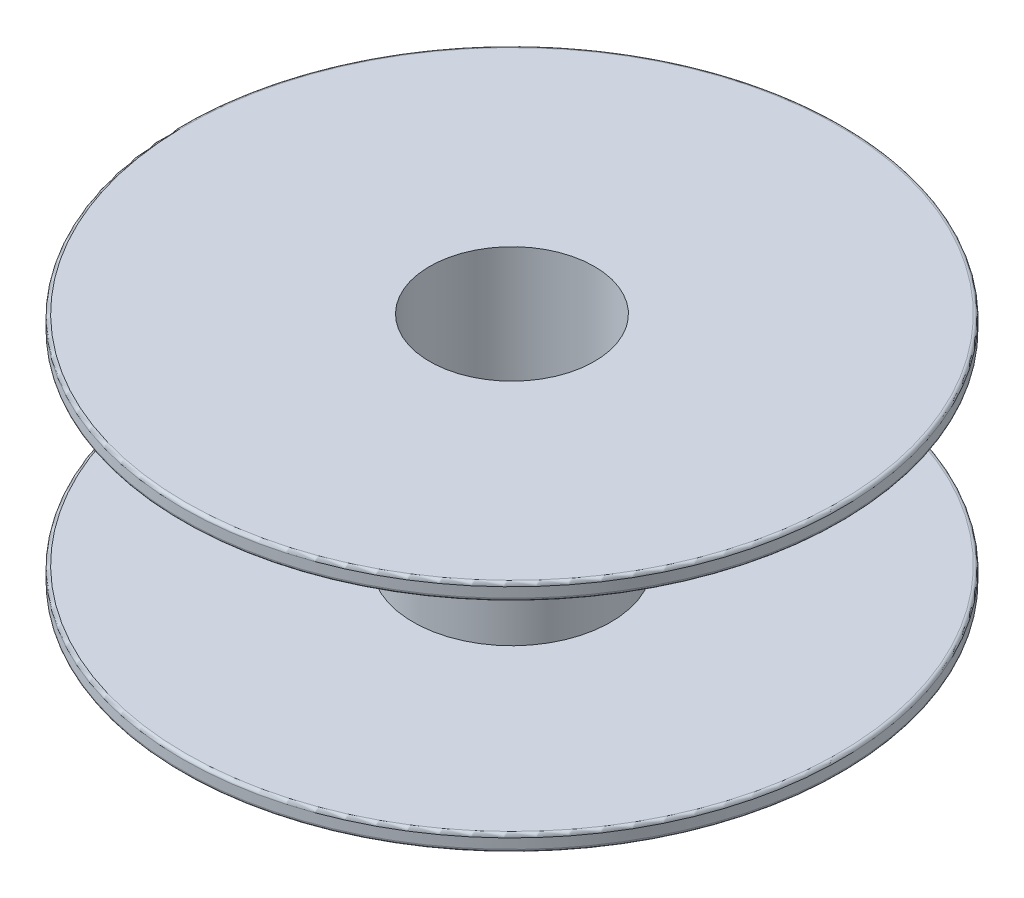
SolidWorks part; units mm, degrees
ref_plane "Front Plane" through (0, 0, 0) normal (0, 0, 1) x (1, 0, 0)
ref_plane "Top Plane" through (0, 0, 0) normal (0, 1, 0) x (1, 0, 0)
ref_plane "Right Plane" through (0, 0, 0) normal (1, 0, 0) x (0, 0, -1)
sketch "Sketch1" plane through (0, 0, 0) normal (1, 0, 0) x (0, 0, -1)
  line L0 (0, 0) -> (0, 71) construction
  line L1 (25, 0) -> (100, 0)
  line L2 (100, 0) -> (100, 5)
  line L3 (100, 5) -> (30, 5)
  line L4 (30, 5) -> (30, 66)
  line L5 (30, 66) -> (100, 66)
  line L6 (100, 66) -> (100, 71)
  line L7 (100, 71) -> (25, 71)
  line L8 (25, 71) -> (25, 0)
  dimension "D1" = 5
  dimension "D2" = 5
  dimension "D3" = 100
  dimension "D4" = 5
  dimension "D5" = 71
  dimension "D6" = 30
revolve "Revolve1" add sketch "Sketch1" angle 360 about L0
fillet "Fillet1" radius 1 4 edges at (0, 0, -100) (0, 5, -100) (0, 66, -100) (0, 71, -100)
